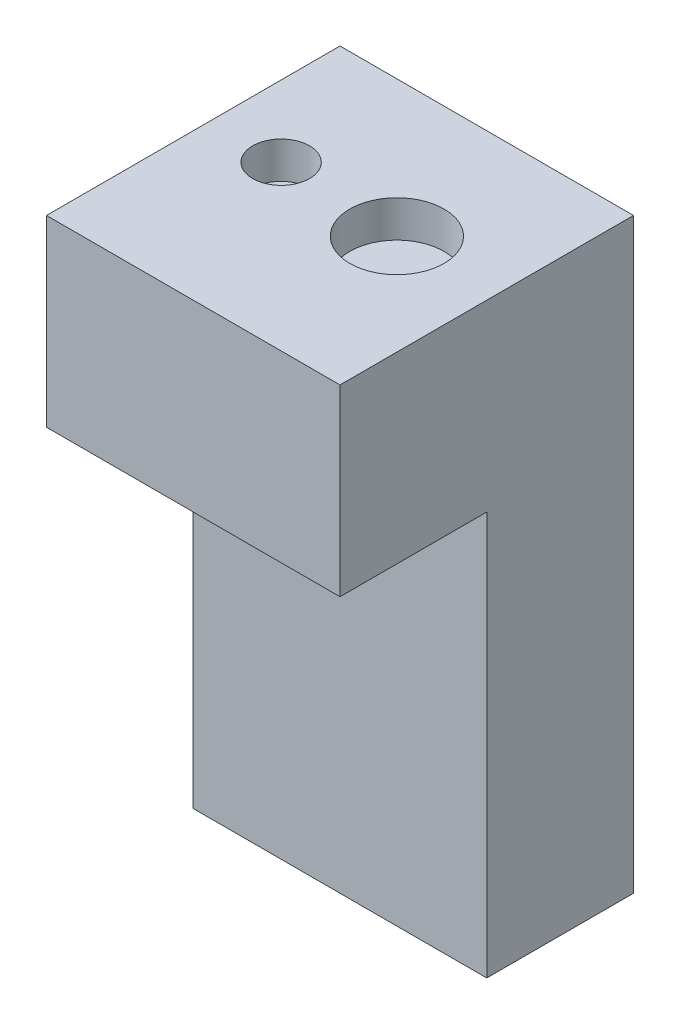
SolidWorks part; units mm, degrees
ref_plane "前视基准面" through (0, 0, 0) normal (0, 0, 1) x (1, 0, 0)
ref_plane "上视基准面" through (0, 0, 0) normal (0, 1, 0) x (1, 0, 0)
ref_plane "右视基准面" through (0, 0, 0) normal (1, 0, 0) x (0, 0, -1)
sketch "草图1" plane through (0, 0, 0) normal (0, 0, 1) x (1, 0, 0)
  line L1 (-20, -40) -> (20, -40)
  line L2 (-20, -40) -> (-20, 40)
  line L3 (-20, 40) -> (20, 40)
  line L4 (20, -40) -> (20, 40)
  line L5 (-20, -40) -> (20, 40) construction
  line L6 (-20, 40) -> (20, -40) construction
  point P0 (0, 0)
extrude "凸台-拉伸1" add sketch "草图1" along normal blind 20
sketch "草图2" plane through (0, 0, 20) normal (0, 0, 1) x (1, 0, 0)
  line L0 (20, -40) -> (20, 40) construction
  line L1 (-20, 40) -> (20, 40)
  line L2 (-20, 40) -> (-20, 15)
  line L3 (-20, 15) -> (20, 15)
  line L4 (20, 40) -> (20, 15)
extrude "凸台-拉伸2" add sketch "草图2" along normal blind 20
sketch "草图3" plane through (0, 40, 0) normal (0, 1, 0) x (1, 0, 0)
  circle A0 centre (-10.2976, -17.7229) radius 3.8734
  circle A1 centre (6.3297, -18.5732) radius 6.4242
extrude "切除-拉伸1" cut sketch "草图3" against normal blind 5
